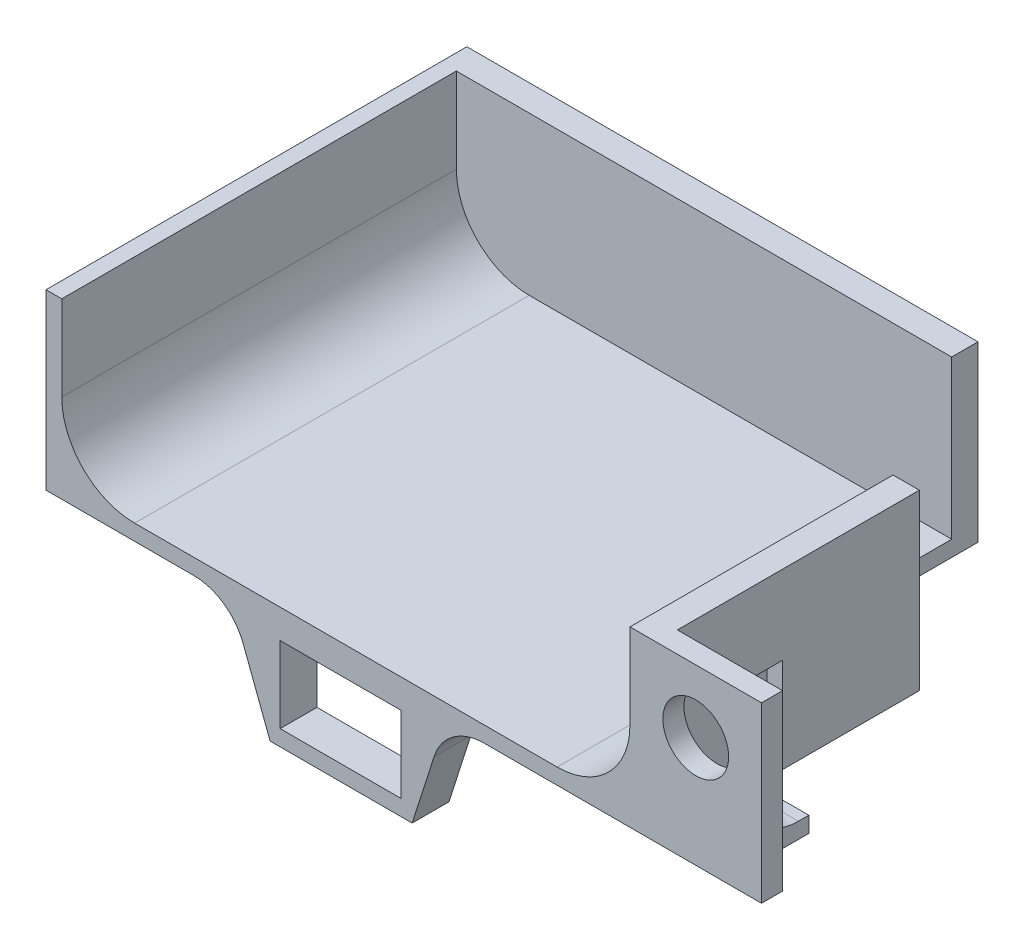
SolidWorks part; units mm, degrees
ref_plane "Plan de face" through (0, 0, 0) normal (0, 0, 1) x (1, 0, 0)
ref_plane "Plan de dessus" through (0, 0, 0) normal (0, 1, 0) x (1, 0, 0)
ref_plane "Plan de droite" through (0, 0, 0) normal (1, 0, 0) x (0, 0, -1)
sketch "Esquisse1" plane through (0, 0, 0) normal (0, 1, 0) x (1, 0, 0)
  line L1 (0, 0) -> (138, 0)
  line L2 (0, 0) -> (0, 75)
  line L3 (0, 75) -> (138, 75)
  line L4 (138, 0) -> (138, 75)
  dimension "D1" = 138
  dimension "D2" = 75
extrude "Boss.-Extru.1" add sketch "Esquisse1" along normal blind 3
sketch "Esquisse2" plane through (0, 3, 0) normal (0, 1, 0) x (1, 0, 0)
  line L0 (0, 0) -> (138, 0) construction
  line L1 (0, 75) -> (5, 75)
  line L2 (0, 75) -> (0, 0)
  line L3 (0, 0) -> (5, 0)
  line L4 (5, 75) -> (5, 0)
  line L6 (138, 75) -> (113, 75)
  line L7 (138, 75) -> (138, 0)
  line L8 (138, 0) -> (113, 0)
  line L9 (113, 75) -> (113, 0)
  dimension "D1" = 25
  dimension "D2" = 5
extrude "Boss.-Extru.2" add sketch "Esquisse2" along normal blind 30
fillet "Congé1" radius 13.85 2 edges at (113, 3, -37.5) (5, 3, -37.5)
sketch "Esquisse3" plane through (0, 0, -75) normal (0, 0, -1) x (-1, 0, 0)
  line L1 (-138, 0) -> (0, 0)
  line L2 (-138, 0) -> (-138, 33)
  line L3 (-138, 33) -> (0, 33)
  line L4 (0, 0) -> (0, 33)
extrude "Boss.-Extru.3" add sketch "Esquisse3" along normal blind 5
sketch "Esquisse4" plane through (0, 0, 0) normal (-1, 0, 0) x (0, 0, 1)
  line L1 (0, 33) -> (-25, 33)
  line L2 (0, 33) -> (0, 13)
  line L3 (0, 13) -> (-25, 13)
  line L4 (-25, 33) -> (-25, 13)
  dimension "D1" = 25
  dimension "D2" = 20
extrude "Enlèv. mat.-Extru.1" [suppressed] cut sketch "Esquisse4" against normal blind 6
sketch "Esquisse5" plane through (0, 33, 0) normal (0, 1, 0) x (1, 0, 0)
  line L0 (113, 75) -> (113, 0) construction
  line L1 (138, 80) -> (118, 80)
  line L2 (138, 80) -> (138, 4)
  line L3 (138, 4) -> (118, 4)
  line L4 (118, 80) -> (118, 4)
  line L5 (113, 0) -> (138, 0) construction
  dimension "D1" = 5
  dimension "D2" = 4
extrude "Enlèv. mat.-Extru.2" cut sketch "Esquisse5" against normal blind 30
sketch "Esquisse6" plane through (0, 0, 0) normal (0, 0, 1) x (1, 0, 0)
  line L0 (113, 33) -> (138, 33) construction
  line L3 (138, 33) -> (138, 0) construction
  circle A0 centre (125.5, 21) radius 6.25
  dimension "D3" = 12.5
  dimension "D1" = 12
  dimension "D2" = 12.5
extrude "Enlèv. mat.-Extru.3" cut sketch "Esquisse6" against normal up to surface (4 mm away) up to face at (128, 18, -4)
sketch "Esquisse7" plane through (0, 0, -80) normal (0, 0, -1) x (-1, 0, 0)
  line L1 (-138, 0) -> (-118, 0)
  line L2 (-138, 0) -> (-138, 3)
  line L3 (-138, 3) -> (-118, 3)
  line L4 (-118, 0) -> (-118, 3)
extrude "Enlèv. mat.-Extru.4" cut sketch "Esquisse7" against normal blind 30
sketch "Esquisse8" plane through (0, 33, 0) normal (0, 1, 0) x (1, 0, 0)
  line L0 (99.15, 0) -> (99.15, 75) construction
  line L1 (118, 80) -> (99.15, 80)
  line L2 (118, 80) -> (118, 50)
  line L3 (118, 50) -> (99.15, 50)
  line L4 (99.15, 80) -> (99.15, 50)
  dimension "D1" = 30
extrude "Enlèv. mat.-Extru.5" cut sketch "Esquisse8" against normal up to surface (33 mm away) up to face at (85.3333, 0, -43.3333)
sketch "Esquisse10" plane through (118, 0, 0) normal (1, 0, 0) x (0, 0, -1)
  line L0 (50, 3) -> (4, 3) construction
  line L1 (16, 3) -> (24, 3)
  line L2 (16, 3) -> (16, 18)
  line L3 (16, 18) -> (24, 18)
  line L4 (24, 3) -> (24, 18)
  dimension "D1" = 12
  dimension "D2" = 8
  dimension "D3" = 15
extrude "Enlèv. mat.-Extru.6" cut sketch "Esquisse10" against normal offset from surface (3 mm away) 2 up to face at (113, 24.925, -25)
sketch "Esquisse11" plane through (0, 3, 0) normal (0, 1, 0) x (1, 0, 0)
  line L1 (115, 24) -> (118, 24)
  line L2 (115, 24) -> (115, 16)
  line L3 (115, 16) -> (131, 16)
  line L8 (138, 4) -> (131, 4)
  line L9 (131, 16) -> (131, 4)
  line L10 (138, 50) -> (138, 4)
  line L11 (118, 50) -> (138, 50)
  line L12 (118, 50) -> (118, 24)
  dimension "D1" = 12
  dimension "D2" = 7
  dimension "D3" = 20
extrude "Enlèv. mat.-Extru.7" cut sketch "Esquisse11" against normal up to surface (3 mm away) up to face at (79.05, 0, -43.3333)
sketch "Esquisse12" plane through (0, 0, 0) normal (-1, 0, 0) x (0, 0, 1)
  line L1 (-80, 33) -> (0, 33)
  line L2 (-80, 33) -> (-80, 0)
  line L3 (-80, 0) -> (0, 0)
  line L4 (0, 33) -> (0, 0)
extrude "Enlèv. mat.-Extru.8" cut sketch "Esquisse12" against normal blind 2
sketch "Esquisse13" plane through (0, 0, 0) normal (0, 0, 1) x (1, 0, 0)
  line L0 (37, 0) -> (44.5969, -20)
  line L1 (2, 0) -> (138, 0) construction
  line L2 (44.5969, -20) -> (71.5969, -20)
  line L3 (71.5969, -20) -> (78, 0)
  line L4 (78, 0) -> (37, 0)
  line L7 (113, 33) -> (113, 16.85) construction
  point P5 (0, 0)
  point P9 (113, 18.5712)
  dimension "D1" = 35
  dimension "D2" = 27
  dimension "D3" = 35
  dimension "D4" = 20
  dimension "D5" = 21
extrude "Boss.-Extru.4" add sketch "Esquisse13" against normal blind 7
sketch "Esquisse14" plane through (0, 0, 0) normal (0, 0, 1) x (1, 0, 0)
  line L0 (44.5969, -20) -> (71.5969, -20) construction
  line L1 (46.5, -2.5) -> (69.5, -2.5)
  line L2 (46.5, -2.5) -> (46.5, -17)
  line L3 (46.5, -17) -> (69.5, -17)
  line L4 (69.5, -2.5) -> (69.5, -17)
  dimension "D1" = 23
  dimension "D2" = 9.5
  dimension "D3" = 3
  dimension "D4" = 14.5
extrude "Enlèv. mat.-Extru.9" cut sketch "Esquisse14" against normal up to surface (7 mm away) up to face at (57.7984, -10, -7)
fillet "Congé2" radius 10 3 edges at (124.5, 3, -4) (78, 0, -3.5) (37, 0, -3.5)
